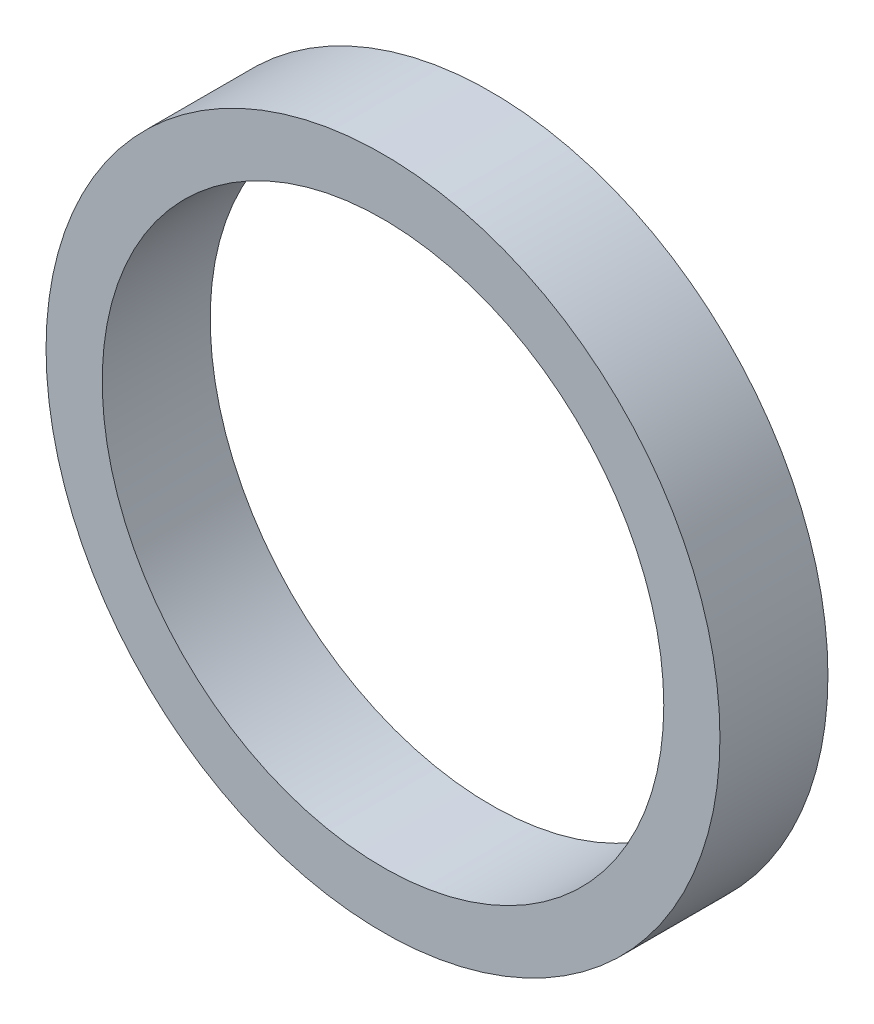
SolidWorks part; units mm, degrees
ref_plane "Alzado" through (0, 0, 0) normal (0, 0, 1) x (1, 0, 0)
ref_plane "Planta" through (0, 0, 0) normal (0, 1, 0) x (1, 0, 0)
ref_plane "Vista lateral" through (0, 0, 0) normal (1, 0, 0) x (0, 0, -1)
sketch "Croquis1" plane through (0, 0, 0) normal (0, 0, 1) x (1, 0, 0)
  circle A0 centre (0, 0) radius 15.6
  circle A1 centre (0, 0) radius 13
extrude "Saliente-Extruir1" add sketch "Croquis1" along normal blind 5
